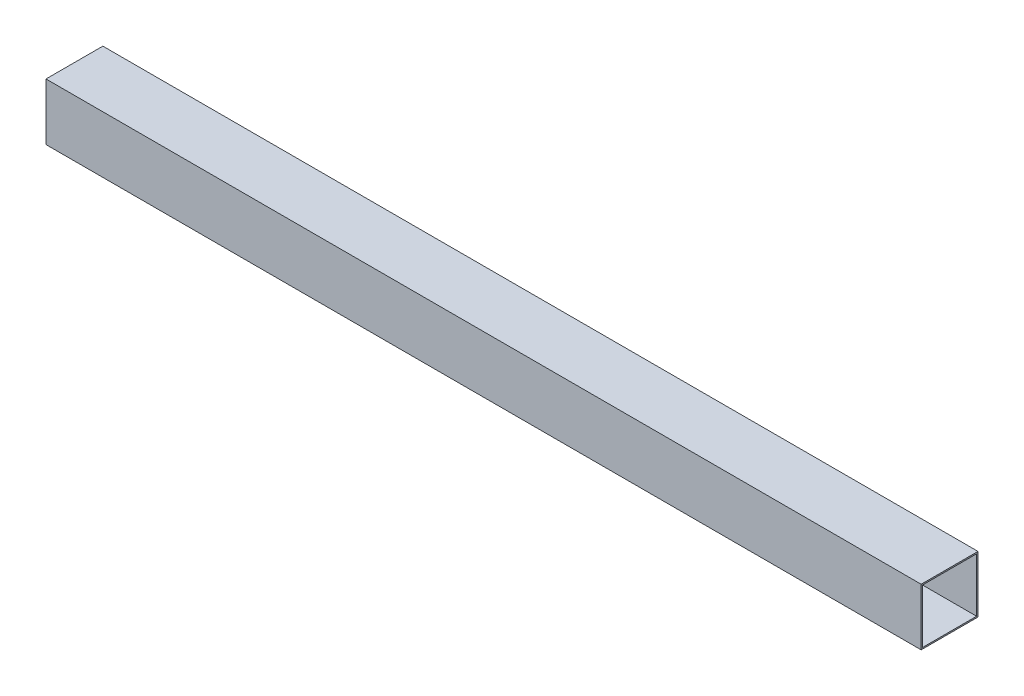
SolidWorks part; units mm, degrees
ref_plane "Alzado" through (0, 0, 0) normal (0, 0, 1) x (1, 0, 0)
ref_plane "Planta" through (0, 0, 0) normal (0, 1, 0) x (1, 0, 0)
ref_plane "Vista lateral" through (0, 0, 0) normal (1, 0, 0) x (0, 0, -1)
sketch "Croquis1" plane through (0, 0, 0) normal (0, 0, 1) x (1, 0, 0)
  line L0 (0, 0) -> (782, 0)
  dimension "D1" = 782
other "Al tube (square) 2 SQ X .049 WALL(1)"
ref_plane "Plano1" through (0, 0, 0) normal (1, 0, 0) x (0, 1, 0)
sketch "Sketch1" plane through (0, 0, 0) normal (1, 0, 0) x (0, 1, 0)
  line L0 (-24.1554, -24.1554) -> (-24.1554, 24.1554)
  line L1 (24.1554, 24.1554) -> (-24.1554, 24.1554)
  line L2 (24.1554, 24.1554) -> (24.1554, -24.1554)
  line L3 (-24.1554, -24.1554) -> (24.1554, -24.1554)
  line L4 (-25.4, -25.4) -> (25.4, -25.4)
  line L5 (-25.4, -25.4) -> (-25.4, 25.4)
  line L6 (25.4, 25.4) -> (-25.4, 25.4)
  line L7 (25.4, 25.4) -> (25.4, -25.4)
  line L8 (0, -24.1554) -> (0, -25.4) construction
  line L9 (0, -24.1554) -> (0, 24.1554) construction
  line L10 (0, 24.1554) -> (0, 25.4) construction
  line L11 (25.4, 0) -> (24.1554, 0) construction
  line L12 (24.1554, 0) -> (-24.1554, 0) construction
  line L13 (-24.1554, 0) -> (-25.4, 0) construction
  point P14 (0, 0)
  dimension "Thickness" = 1.2446
  dimension "V_leg" = 50.8
  dimension "H_leg" = 50.8
